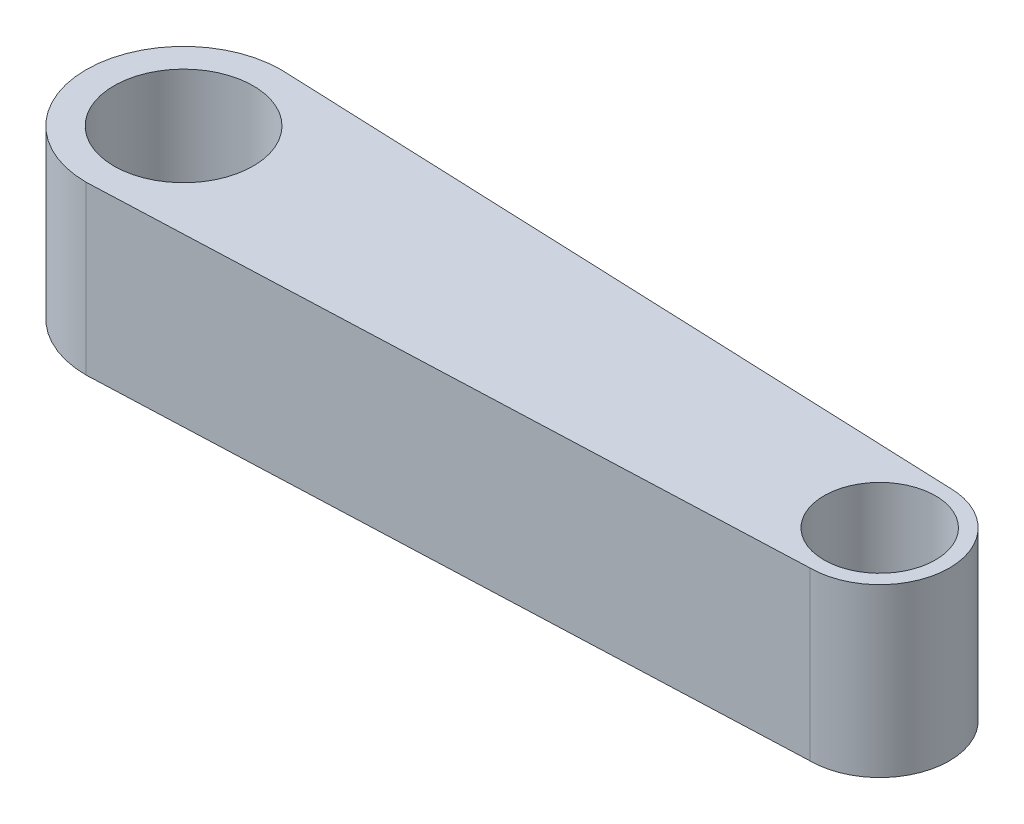
SolidWorks part; units mm, degrees
ref_plane "Front Plane" through (0, 0, 0) normal (0, 0, 1) x (1, 0, 0)
ref_plane "Top Plane" through (0, 0, 0) normal (0, 1, 0) x (1, 0, 0)
ref_plane "Right Plane" through (0, 0, 0) normal (1, 0, 0) x (0, 0, -1)
sketch "Sketch2" plane through (0, 0, 0) normal (0, 1, 0) x (1, 0, 0)
  line L0 (0, 35) -> (250, 25)
  line L1 (0, -35) -> (250, -25)
  arc A0 (0, 35) -> (0, -35) centre (0, 0) ccw
  arc A1 (250, -25) -> (250, 25) centre (250, 0) ccw
  dimension "D1" = 70
  dimension "D2" = 50
  dimension "D3" = 250
extrude "Boss-Extrude1" add sketch "Sketch2" along normal blind 60
sketch "Sketch3" plane through (0, 60, 0) normal (0, 1, 0) x (1, 0, 0)
  circle A0 centre (0, 0) radius 25
  circle A1 centre (250, 0) radius 20
  dimension "D1" = 50
  dimension "D2" = 40
extrude "Cut-Extrude1" cut sketch "Sketch3" against normal blind 50
